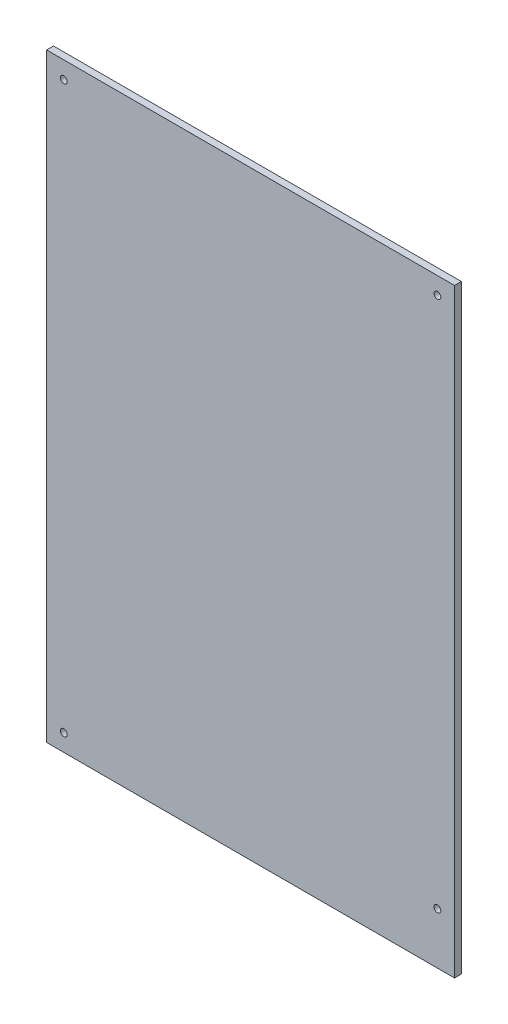
SolidWorks part; units mm, degrees
material "Sklo"
ref_plane "Přední rovina" through (0, 0, 0) normal (0, 0, 1) x (1, 0, 0)
ref_plane "Horní rovina" through (0, 0, 0) normal (0, 1, 0) x (1, 0, 0)
ref_plane "Pravá rovina" through (0, 0, 0) normal (1, 0, 0) x (0, 0, -1)
sketch "Skica1" plane through (0, 0, 0) normal (0, 0, 1) x (1, 0, 0)
  line L1 (119, -175) -> (-119, -175)
  line L2 (119, -175) -> (119, 175)
  line L3 (119, 175) -> (-119, 175)
  line L4 (-119, -175) -> (-119, 175)
  line L5 (119, -175) -> (-119, 175) construction
  line L6 (119, 175) -> (-119, -175) construction
  circle A0 centre (109, 165) radius 2
  circle A1 centre (109, -145) radius 2
  circle A2 centre (-109, 165) radius 2
  circle A3 centre (-109, -165) radius 2
  point P0 (0, 0)
  dimension "D3" = 4
  dimension "D1" = 350
  dimension "D2" = 238
  dimension "D4" = 30
  dimension "D5" = 10
  dimension "D6" = 10
  dimension "D7" = 10
  dimension "D8" = 10
  dimension "D9" = 10
  dimension "D10" = 10
  dimension "D11" = 10
extrude "Přidat vysunutím1" add sketch "Skica1" along normal blind 4
